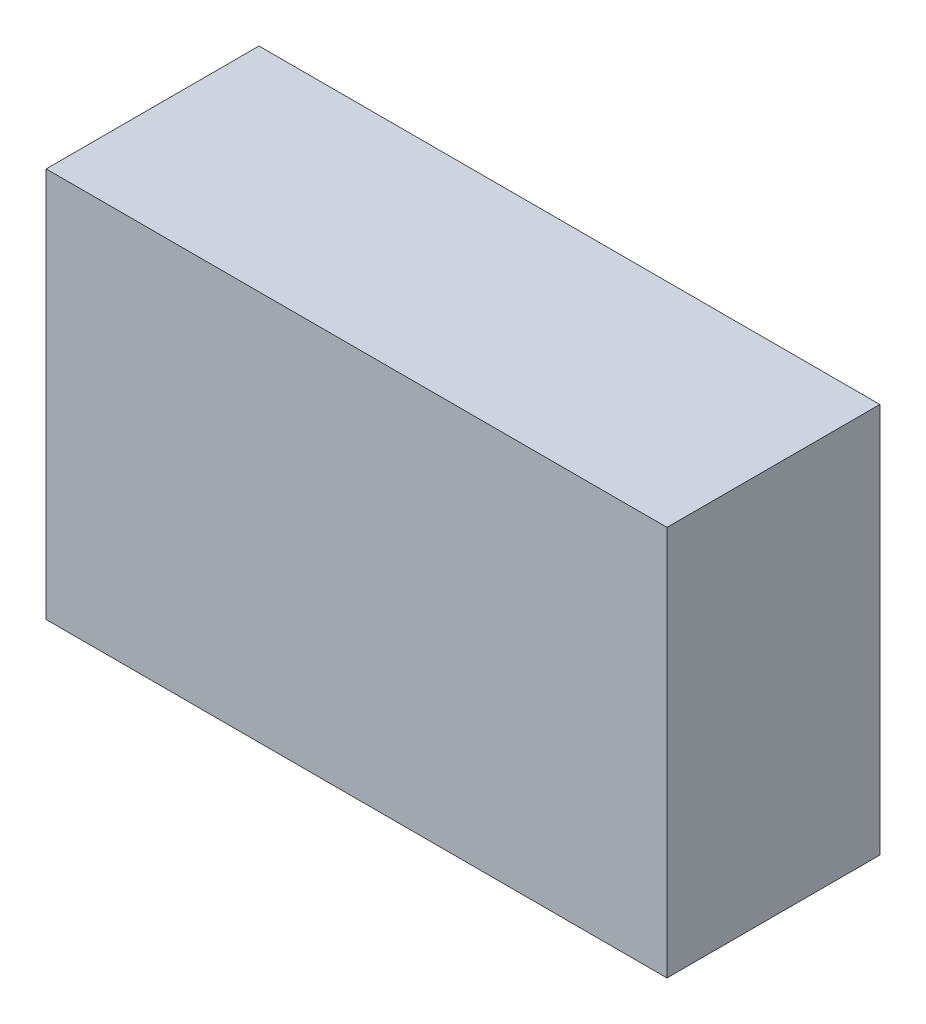
SolidWorks part; units mm, degrees
ref_plane "Front Plane" through (0, 0, 0) normal (0, 0, 1) x (1, 0, 0)
ref_plane "Top Plane" through (0, 0, 0) normal (0, 1, 0) x (1, 0, 0)
ref_plane "Right Plane" through (0, 0, 0) normal (1, 0, 0) x (0, 0, -1)
sketch "Sketch1" plane through (0, 0, 0) normal (0, 0, 1) x (1, 0, 0)
  line L1 (-17.5, 11) -> (17.5, 11)
  line L2 (-17.5, 11) -> (-17.5, -11)
  line L3 (-17.5, -11) -> (17.5, -11)
  line L4 (17.5, 11) -> (17.5, -11)
  line L5 (-17.5, 11) -> (17.5, -11) construction
  line L6 (-17.5, -11) -> (17.5, 11) construction
  point P0 (0, 0)
  dimension "D1" = 35
  dimension "D2" = 22
extrude "Boss-Extrude1" add sketch "Sketch1" along normal blind 12
